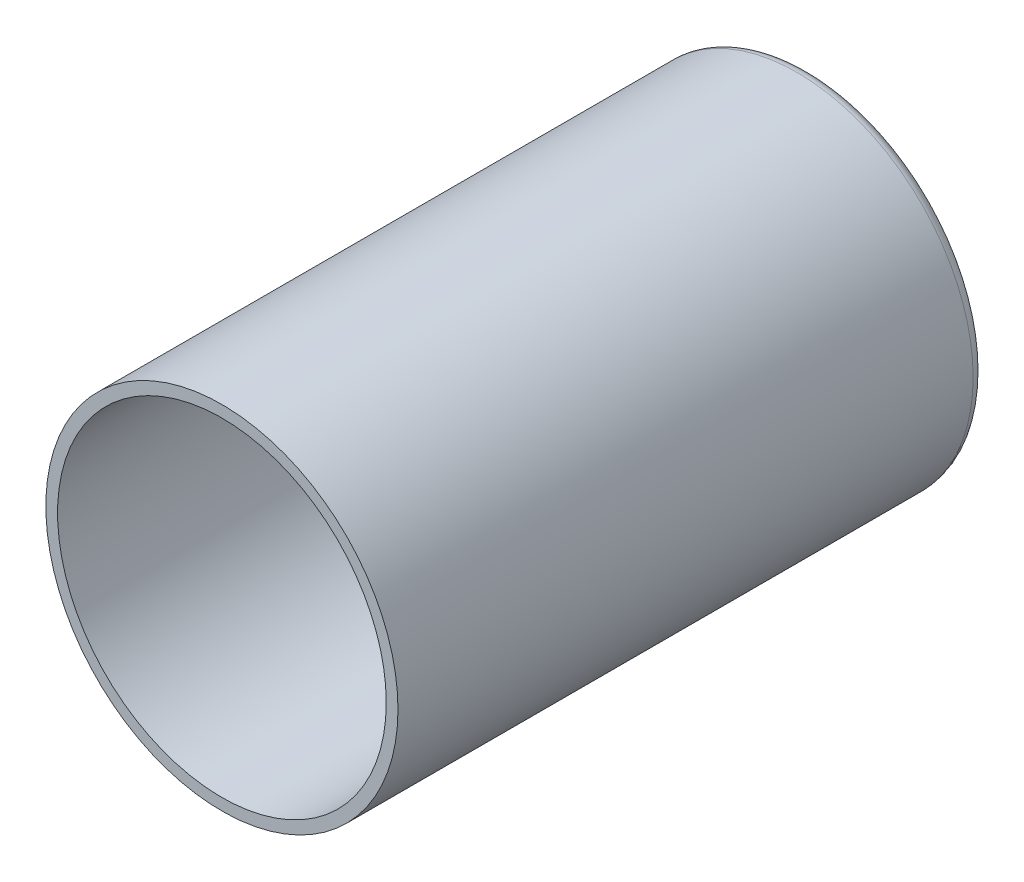
SolidWorks part; units mm, degrees
ref_plane "Front Plane" through (0, 0, 0) normal (0, 0, 1) x (1, 0, 0)
ref_plane "Top Plane" through (0, 0, 0) normal (0, 1, 0) x (1, 0, 0)
ref_plane "Right Plane" through (0, 0, 0) normal (1, 0, 0) x (0, 0, -1)
sketch "Sketch1" plane through (0, 0, 0) normal (0, 0, 1) x (1, 0, 0)
  circle A0 centre (0, 0) radius 30
  dimension "D1" = 60
extrude "Boss-Extrude1" add sketch "Sketch1" along normal blind 100
shell "Shell1" thickness 2
fillet "Fillet1" radius 2 1 edges at (30, 0, 0)
sketch "Sketch2" plane through (0, 0, 0) normal (0, 0, -1) x (-1, 0, 0)
  circle A0 centre (0, 0) radius 10
  dimension "D1" = 20
extrude "Boss-Extrude2" add sketch "Sketch2" along normal blind 5
sketch "Sketch3" plane through (0, 0, -5) normal (0, 0, -1) x (-1, 0, 0)
  circle A0 centre (0, 0) radius 2.5
  dimension "D1" = 5
extrude "Cut-Extrude1" cut sketch "Sketch3" against normal through all
